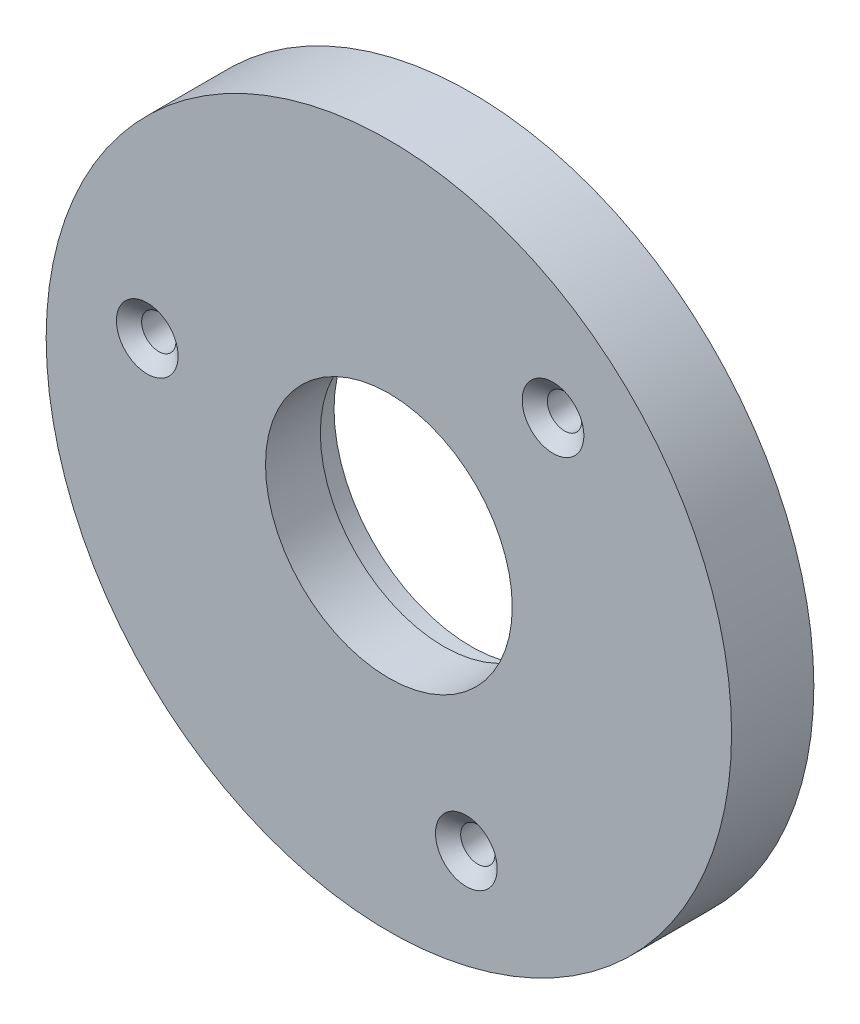
SolidWorks part; units mm, degrees
material "Copper"
ref_plane "Front Plane" through (0, 0, 0) normal (0, 0, 1) x (1, 0, 0)
ref_plane "Top Plane" through (0, 0, 0) normal (0, 1, 0) x (1, 0, 0)
ref_plane "Right Plane" through (0, 0, 0) normal (1, 0, 0) x (0, 0, -1)
sketch "Sketch1" plane through (0, 0, 0) normal (0, 0, 1) x (1, 0, 0)
  circle A0 centre (0, 0) radius 15.875
  dimension "D1" = 31.75
extrude "Boss-Extrude1" add sketch "Sketch1" along normal blind 3.81
sketch "Sketch2" plane through (0, 0, 3.81) normal (0, 0, 1) x (1, 0, 0)
  circle A0 centre (0, 0) radius 5.715
  dimension "D1" = 11.43
extrude "Cut-Extrude1" cut sketch "Sketch2" against normal through all
sketch "Sketch3" plane through (0, 0, 0) normal (0, 0, -1) x (-1, 0, 0)
  circle A0 centre (0, 0) radius 6.35
  dimension "D1" = 12.7
extrude "Cut-Extrude3" cut sketch "Sketch3" against normal blind 1.27 contours A0
sketch "Sketch9" plane through (0, 0, 3.81) normal (0, 0, 1) x (1, 0, 0)
  line L0 (0, -15.875) -> (0, -5.715)
  circle A0 centre (0, 0) radius 15.875 construction
  circle A1 centre (0, 0) radius 5.715 construction
  point P7 (0, -10.795)
sketch "Sketch10" plane through (0, 0, 3.81) normal (0, 0, 1) x (1, 0, 0)
  line L0 (0, 0) -> (7.6048, 8.533)
  dimension "D1" = 11.43
hole_wizard "1/16 (0.0625) Diameter Hole1" positions "Sketch11" profile "Sketch12" hole size "1/16" standard "ANSI Inch" end condition through all
sketch "Sketch11" plane through (0, 0, 3.81) normal (0, 0, 1) x (1, 0, 0)
  point P0 (7.6048, 8.533)
sketch "Sketch12" plane through (7.6048, 8.533, 3.81) normal (1, 0, 0) x (0, -1, 0)
  line L0 (0, 0) -> (0, 3.81)
  line L1 (0, 3.81) -> (0.7937, 3.81)
  line L2 (0.7937, 3.81) -> (0.7937, 0.5328)
  line L3 (0.7937, 0.5328) -> (1.4287, 0)
  line L5 (1.4287, 0) -> (0, 0)
  line L6 (-0.7937, 0.5328) -> (-1.4287, 0) construction
  line L11 (0, -6.35) -> (0, 107.95) construction
  dimension "Thru Hole Dia." = 1.5875
  dimension "Thru Hole Depth" = 3.81
  dimension "Near C'Sink Dia." = 2.8575
  dimension "Near C'Sink Angle" = 100
pattern_circular "CirPattern1" count 3 every 120 about axis through (0, 0, 0) along (0, 0, 1) of "1/16 (0.0625) Diameter Hole1"
